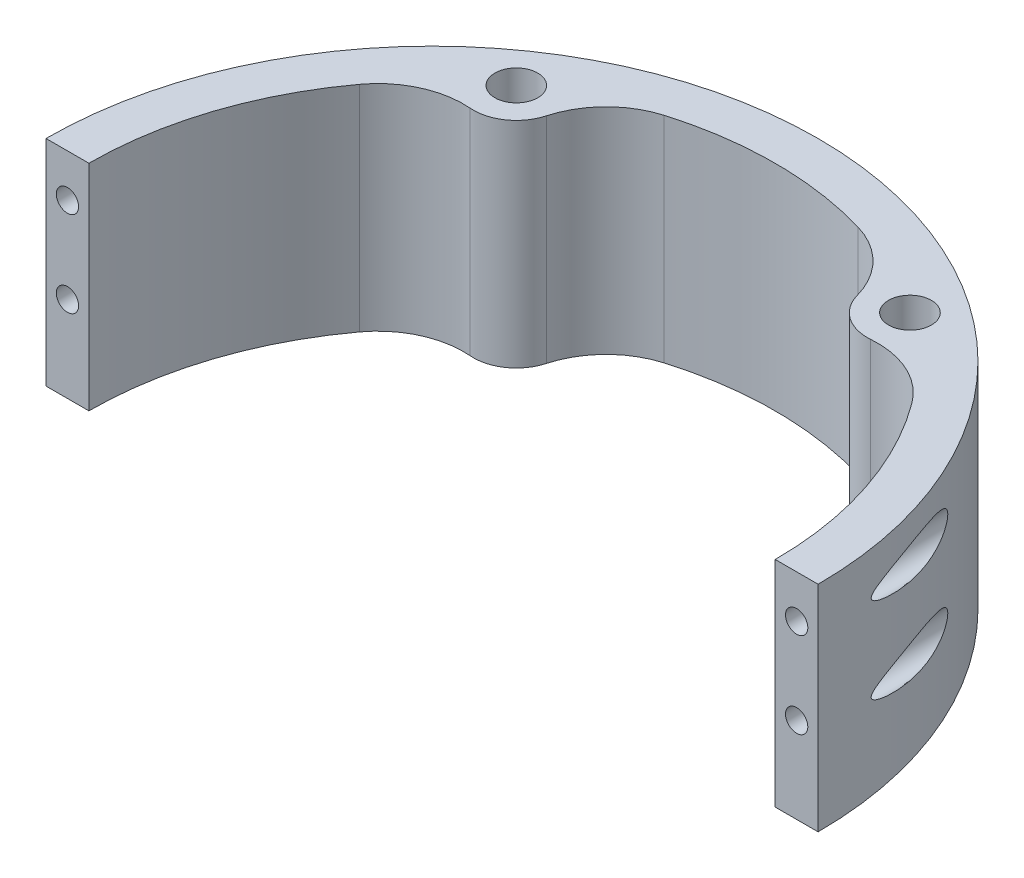
SolidWorks part; units mm, degrees
material "6061 Alloy"
ref_plane "Front Plane" through (0, 0, 0) normal (0, 0, 1) x (1, 0, 0)
ref_plane "Top Plane" through (0, 0, 0) normal (0, 1, 0) x (1, 0, 0)
ref_plane "Right Plane" through (0, 0, 0) normal (1, 0, 0) x (0, 0, -1)
sketch "Sketch1" plane through (0, 0, 0) normal (0, 1, 0) x (1, 0, 0)
  line L2 (-45, 0) -> (-40, 0)
  line L4 (40, 0) -> (45, 0)
  circle A2 centre (0, 0) radius 60 construction
  circle A9 centre (0, 0) radius 45 construction
  arc A11 (-26.8516, 29.6478) -> (26.8516, 29.6478) centre (0, 0) ccw construction
  circle A17 centre (0, 0) radius 32.5 construction
  arc A19 (-40, 0) -> (-26.8516, 29.6478) centre (0, 0) cw
  arc A20 (45, 0) -> (-45, 0) centre (0, 0) ccw
  arc A21 (-18.6761, 35.3724) -> (-26.8516, 29.6478) centre (-22.9431, 32.7661) cw
  circle A24 centre (22.9431, 32.7661) radius 2.5
  circle A25 centre (-22.9431, 32.7661) radius 2.5
  arc A26 (18.6761, 35.3724) -> (-18.6761, 35.3724) centre (0, 0) ccw construction
  arc A27 (26.8516, 29.6478) -> (18.6761, 35.3724) centre (22.9431, 32.7661) cw
  circle A28 centre (0, 0) radius 35 construction
  arc A29 (-18.6761, 35.3724) -> (18.6761, 35.3724) centre (0, 0) cw
  arc A30 (-22.9431, 32.7661) -> (0, 40) centre (0, 0) cw construction
  arc A31 (26.8516, 29.6478) -> (40, 0) centre (0, 0) cw
  dimension "D1" = 120
  dimension "D2" = 80
  dimension "D3" = 90
  dimension "D4" = 65
  dimension "D5" = 5
  dimension "D7" = 40
  dimension "D8" = 70
  dimension "D6" = 5
  dimension "D9" = 35
extrude "Boss-Extrude1" add sketch "Sketch1" along normal blind 25
sketch "Sketch6" plane through (0, 0, 0) normal (0, 0, 1) x (1, 0, 0)
  line L0 (-42.5, 0) -> (-42.5, 10) construction
  line L1 (-42.5, 10) -> (-42.5, 20) construction
  line L2 (42.5, 0) -> (42.5, 10) construction
  line L3 (42.5, 10) -> (42.5, 20) construction
  circle A0 centre (-42.5, 20) radius 2
  circle A1 centre (-42.5, 10) radius 2
  circle A2 centre (42.5, 20) radius 2
  circle A3 centre (42.5, 10) radius 2
extrude "Cut-Extrude3" cut sketch "Sketch6" against normal through all from offset 5 offset against normal yes
sketch "Sketch7" plane through (0, 0, 0) normal (0, 0, 1) x (1, 0, 0)
  line L0 (-42.5, 0) -> (-42.5, 10) construction
  line L1 (-42.5, 10) -> (-42.5, 20) construction
  line L2 (42.5, 0) -> (42.5, 10) construction
  line L3 (42.5, 10) -> (42.5, 20) construction
  circle A0 centre (-42.5, 20) radius 1
  circle A1 centre (-42.5, 10) radius 1
  circle A2 centre (42.5, 10) radius 1
  circle A3 centre (42.5, 20) radius 1
extrude "Cut-Extrude4" cut sketch "Sketch7" against normal through all
fillet "Fillet1" radius 10 4 edges at (26.8516, 12.5, -29.6478) (18.6761, 12.5, -35.3724) (-18.6761, 12.5, -35.3724) (-26.8516, 12.5, -29.6478)
hole_wizard "CSK for M2 Flat Head Machine Screw1" positions "3DSketch2" profile "Sketch17" countersink size "M2" standard "ANSI Metric"
sketch3d "3DSketch2"
  line L0 (42.5, 20, -5) -> (42.5, 20, 0) construction
  line L1 (42.5, 20, -19.615) -> (42.5, 20, -5) construction
  line L2 (42.5, 10, -5) -> (42.5, 10, 0) construction
  line L3 (-42.5, 20, -5) -> (-42.5, 20, 0) construction
  line L4 (-42.5, 10, -5) -> (-42.5, 10, 0) construction
  line L5 (-42.5, 10, -6.6986) -> (-42.5, 10, -5) construction
  point P0 (42.5, 20, -5)
  point P6 (42.5, 10, -5)
  point P10 (-42.5, 20, -5)
  point P14 (-42.5, 10, -5)
sketch "Sketch17" plane through (-42.5, 20, -5) normal (1, 0, 0) x (0, 1, 0)
  line L0 (0, 0) -> (0, 5)
  line L1 (0, 5) -> (1.3, 5)
  line L2 (1.3, 5) -> (1.3, 0.9)
  line L3 (1.3, 0.9) -> (2.2, 0)
  line L5 (2.2, 0) -> (0, 0)
  line L6 (-1.3, 0.9) -> (-2.2, 0) construction
  line L11 (0, -6.35) -> (0, 107.95) construction
  dimension "Thru Hole Dia." = 2.6
  dimension "Thru Hole Depth" = 5
  dimension "Near C'Sink Dia." = 4.4
  dimension "Near C'Sink Angle" = 90
hole_wizard "CSK for M2 Flat Head Machine Screw2" positions "3DSketch3" profile "Sketch18" countersink size "M2" standard "ANSI Metric"
sketch3d "3DSketch3"
  line L0 (42.5, 20, -5) -> (42.5, 20, 0) construction
  line L1 (-42.5, 10, -5) -> (-42.5, 10, 0) construction
  point P0 (42.5, 20, -5)
  point P4 (-42.5, 10, -5)
sketch "Sketch18" plane through (42.5, 20, -5) normal (1, 0, 0) x (0, 1, 0)
  line L0 (0, 0) -> (0, 5)
  line L1 (0, 5) -> (1.3, 5)
  line L2 (1.3, 5) -> (1.3, 0.9)
  line L3 (1.3, 0.9) -> (2.2, 0)
  line L5 (2.2, 0) -> (0, 0)
  line L6 (-1.3, 0.9) -> (-2.2, 0) construction
  line L11 (0, -6.35) -> (0, 107.95) construction
  dimension "Thru Hole Dia." = 2.6
  dimension "Thru Hole Depth" = 5
  dimension "Near C'Sink Dia." = 4.4
  dimension "Near C'Sink Angle" = 90
